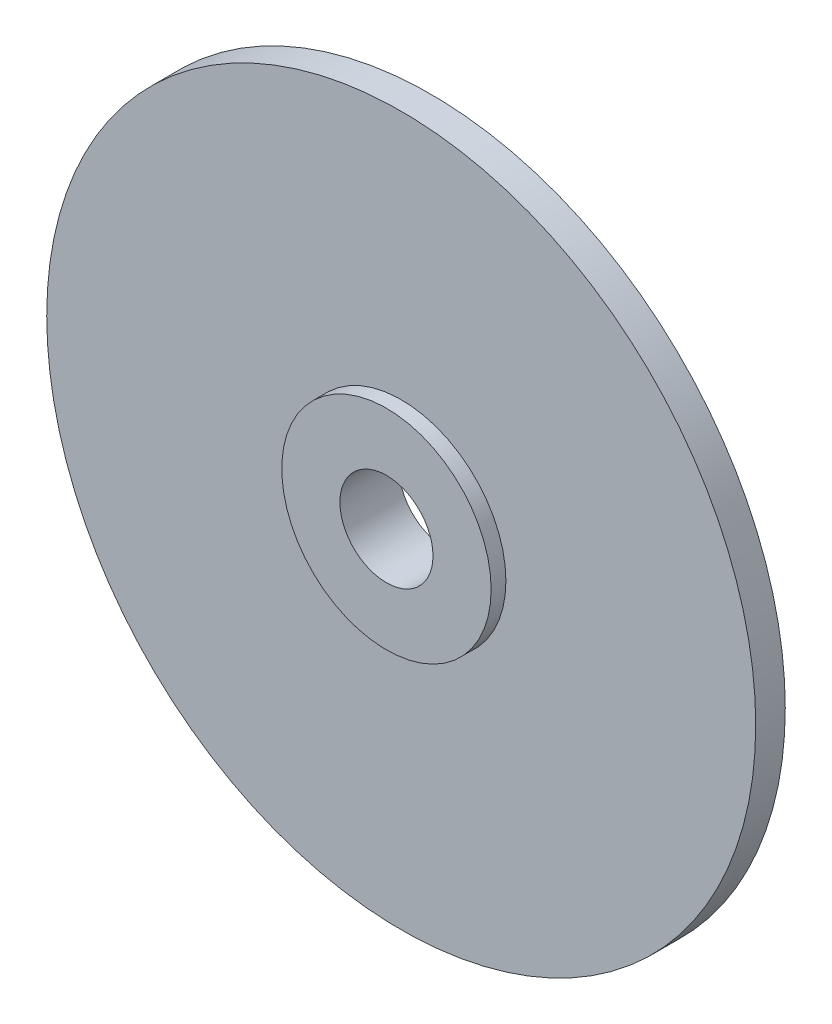
SolidWorks part; units mm, degrees
ref_plane "Front Plane" through (0, 0, 0) normal (0, 0, 1) x (1, 0, 0)
ref_plane "Top Plane" through (0, 0, 0) normal (0, 1, 0) x (1, 0, 0)
ref_plane "Right Plane" through (0, 0, 0) normal (1, 0, 0) x (0, 0, -1)
sketch "Sketch1" plane through (0, 0, 0) normal (0, 0, 1) x (1, 0, 0)
  circle A0 centre (0, 0) radius 152.4
  circle A1 centre (0, 0) radius 20
  dimension "D1" = 304.8
  dimension "D2" = 40
extrude "Boss-Extrude1" add sketch "Sketch1" along normal blind 12.7
sketch "Sketch2" plane through (0, 0, 12.7) normal (0, 0, 1) x (1, 0, 0)
  circle A0 centre (0, 0) radius 45
  circle A1 centre (0, 0) radius 20
  dimension "D1" = 40
  dimension "D2" = 90
extrude "Boss-Extrude2" add sketch "Sketch2" along normal blind 6.35
sketch "Sketch3" plane through (0, 0, 0) normal (0, 0, -1) x (-1, 0, 0)
  circle A0 centre (0, 0) radius 45
  circle A1 centre (0, 0) radius 20
  dimension "D1" = 40
  dimension "D2" = 90
extrude "Boss-Extrude3" add sketch "Sketch3" along normal blind 6.35
